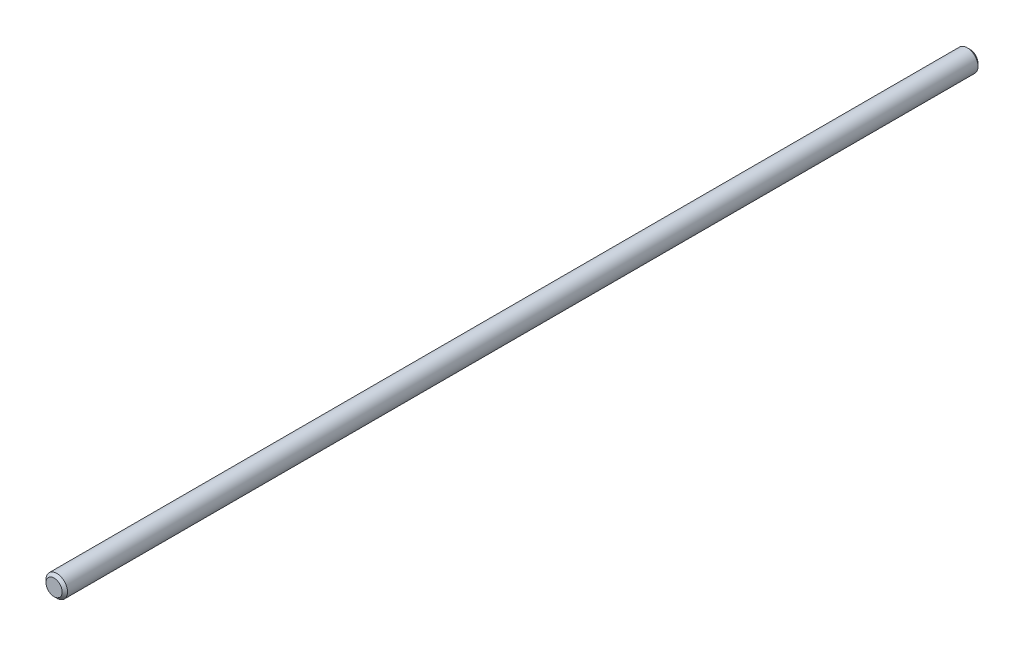
SolidWorks part; units mm, degrees
ref_plane "前视基准面" through (0, 0, 0) normal (0, 0, 1) x (1, 0, 0)
ref_plane "上视基准面" through (0, 0, 0) normal (0, 1, 0) x (1, 0, 0)
ref_plane "右视基准面" through (0, 0, 0) normal (1, 0, 0) x (0, 0, -1)
sketch "草图1" plane through (0, 0, 0) normal (0, 0, 1) x (1, 0, 0)
  circle A0 centre (0, 0) radius 2
extrude "凸台-拉伸1" add sketch "草图1" against normal blind 170
chamfer "倒角1" distance 0.5 angle 45 2 edges at (2, 0, -170) (2, 0, 0)
